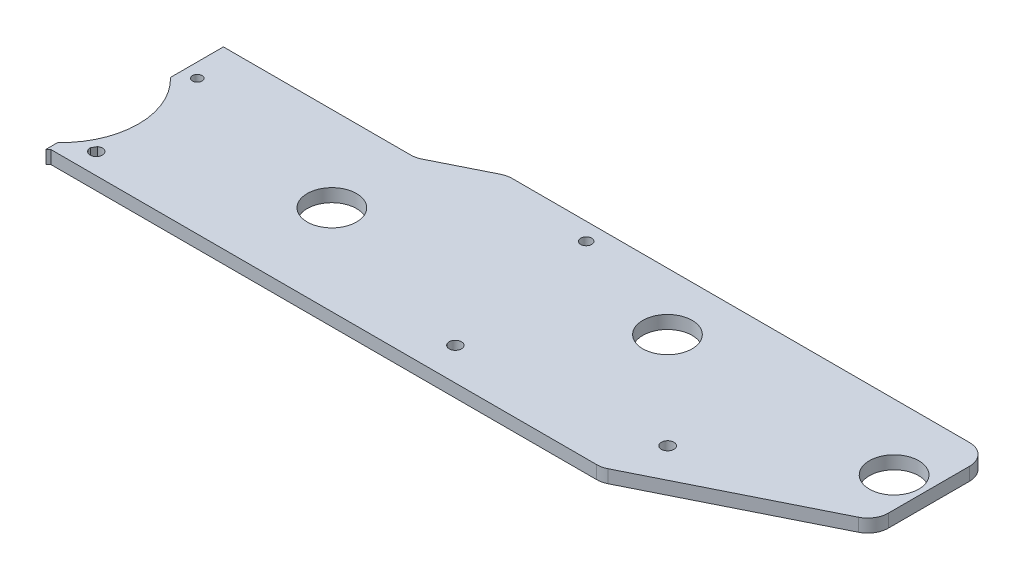
SolidWorks part; units mm, degrees
ref_plane "Front" through (0, 0, 0) normal (0, 0, 1) x (1, 0, 0)
ref_plane "Top" through (0, 0, 0) normal (0, 1, 0) x (1, 0, 0)
ref_plane "Right" through (0, 0, 0) normal (1, 0, 0) x (0, 0, -1)
sketch "Sketch1" plane through (0, 0, 0) normal (0, 1, 0) x (1, 0, 0)
  line L1 (0, 0) -> (210, 0)
  line L2 (0, 0) -> (0, -50)
  line L3 (0, -50) -> (210, -50)
  line L4 (210, 0) -> (210, -50)
  circle A7 centre (3.4895, -16.7877) radius 1.2117
  circle A8 centre (34.3726, -17.194) radius 1.1656
  circle A9 centre (37.5207, -44.9212) radius 1.5
  circle A12 centre (168.9752, -37.4032) radius 1.5173
  circle A13 centre (116, -4.2372) radius 1.3356
  circle A14 centre (12.2576, -3.2748) radius 1.6244
  dimension "D1" = 210
  dimension "D2" = 50
extrude "Boss-Extrude1" add sketch "Sketch1" along normal blind 3.175
sketch "Sketch2" plane through (0, 3.175, 0) normal (0, 1, 0) x (1, 0, 0)
  line L0 (210, 0) -> (0, 0) construction
  line L1 (0, 0) -> (0, -50) construction
  circle A0 centre (10, -26) radius 2
  circle A1 centre (10, -42) radius 2
  circle A2 centre (26, -26) radius 2
  circle A3 centre (26, -42) radius 2
  dimension "D1" = 16
  dimension "D2" = 16
  dimension "D3" = 16
  dimension "D4" = 26
  dimension "D5" = 10
  dimension "D6" = 10
  dimension "D7" = 26
  dimension "D8" = 16
extrude "Cut-Extrude1" cut sketch "Sketch2" against normal blind 10
sketch "Sketch3" plane through (0, 3.175, 0) normal (0, 1, 0) x (1, 0, 0)
  line L0 (210, 0) -> (0, 0) construction
  line L1 (210, 0) -> (0, 0) construction
  circle A0 centre (78.0103, -28.1) radius 6
  circle A1 centre (145.5313, -14) radius 6
  circle A2 centre (18, -34) radius 0.587
  circle A3 centre (26, -26) radius 2 construction
  circle A4 centre (202.6463, -16) radius 6
  dimension "D1" = 28.1
  dimension "D3" = 16
  dimension "D4" = 14
  dimension "D7" = 125.222
  dimension "D2" = 60.2996
  dimension "D5" = 8
  dimension "D6" = 8
  dimension "D8" = 57.15
extrude "Cut-Extrude2" cut sketch "Sketch3" against normal blind 57.15
sketch "Sketch4" [suppressed] plane through (0, 3.175, 0) normal (0, 1, 0) x (1, 0, 0)
  line L0 (3.4895, -16.7877) -> (18, -34)
  line L1 (3.4895, -20.6627) -> (5.9498, -23.5811)
  line L2 (18, -34) -> (34.3726, -17.194)
  line L3 (34.3726, -17.194) -> (75.8499, -28.1)
  line L4 (75.8499, -28.1) -> (37.5207, -44.9212)
  line L5 (7.3432, -17.194) -> (9.8664, -20.303)
  circle A0 centre (18, -34) radius 15.9299
  circle A1 centre (3.4895, -16.7877) radius 3.8751
  circle A2 centre (34.3726, -17.194) radius 3.7227
  circle A3 centre (37.5207, -44.9212) radius 3.8676
  circle A4 centre (75.8499, -28.1) radius 12.797
  circle A5 centre (112.3021, -4.7393) radius 5.1588
  circle A6 centre (118.879, -40.0177) radius 4.9035
  circle A7 centre (140.772, -16) radius 12.6375
  circle A8 centre (168.9752, -37.4032) radius 4.2066
  circle A9 centre (197.922, -16) radius 12.8
sketch "Sketch5" [suppressed] plane through (0, 3.175, 0) normal (0, 1, 0) x (1, 0, 0)
  line L0 (210, 0) -> (0, 0) construction
  line L2 (-0.6266, -16.7877) -> (37.5207, -16.7877)
  line L3 (-0.6266, -16.7877) -> (-0.6266, -44.9212)
  line L4 (-0.6266, -44.9212) -> (37.5207, -44.9212)
  line L5 (37.5207, -16.7877) -> (37.5207, -44.9212)
  line L6 (75.8499, -15.182) -> (37.5207, -15.182)
  line L7 (75.8499, -15.182) -> (75.8499, -44.9212)
  line L8 (75.8499, -44.9212) -> (37.5207, -44.9212)
  line L9 (37.5207, -15.182) -> (37.5207, -44.9212)
  line L10 (112.3021, -4.7393) -> (75.8499, -4.7393)
  line L11 (112.3021, -4.7393) -> (112.3021, -44.9212)
  line L12 (112.3021, -44.9212) -> (75.8499, -44.9212)
  line L13 (75.8499, -4.7393) -> (75.8499, -44.9212)
  line L14 (112.3021, -4.7393) -> (102.3945, -4.7393)
  line L16 (112.3021, -4.7393) -> (112.3021, 0)
  line L17 (112.3021, 0) -> (102.3945, 0)
  line L18 (102.3945, -4.7393) -> (102.3945, 0)
  line L19 (210, -50) -> (210, 0) construction
  line L20 (112.3021, -4.7393) -> (123.1553, -4.7393)
  line L21 (112.3021, -4.7393) -> (112.3021, 0)
  line L22 (112.3021, 0) -> (123.1553, 0)
  line L23 (123.1553, -4.7393) -> (123.1553, 0)
  line L24 (112.3021, -4.7393) -> (140.772, -4.7393)
  line L25 (112.3021, -4.7393) -> (112.3021, -40.0177)
  line L26 (112.3021, -40.0177) -> (140.772, -40.0177)
  line L27 (140.772, -4.7393) -> (140.772, -40.0177)
  line L28 (140.772, -16) -> (168.9752, -16)
  line L29 (140.772, -16) -> (140.772, -40.0177)
  line L30 (140.772, -40.0177) -> (168.9752, -40.0177)
  line L31 (168.9752, -16) -> (168.9752, -40.0177)
  line L32 (168.9752, -4.7393) -> (210, -4.7393)
  line L33 (168.9752, -4.7393) -> (168.9752, -40.0177)
  line L34 (168.9752, -40.0177) -> (210, -40.0177)
  line L35 (210, -4.7393) -> (210, -40.0177)
  line L36 (0, -50) -> (210, -50) construction
  line L37 (160.7629, -40.0177) -> (177.2091, -40.0177)
  line L38 (160.7629, -40.0177) -> (160.7629, -44.9212)
  line L39 (160.7629, -44.9212) -> (177.2091, -44.9212)
  line L40 (177.2091, -40.0177) -> (177.2091, -44.9212)
  line L41 (112.3021, -40.0177) -> (126.3591, -40.0177)
  line L42 (112.3021, -40.0177) -> (112.3021, -47.7828)
  line L43 (112.3021, -47.7828) -> (126.3591, -47.7828)
  line L44 (126.3591, -40.0177) -> (126.3591, -47.7828)
  line L45 (30.5963, -44.9212) -> (44.6115, -44.9212)
  line L46 (30.5963, -44.9212) -> (30.5963, -50)
  line L47 (30.5963, -50) -> (44.6115, -50)
  line L48 (44.6115, -44.9212) -> (44.6115, -50)
  line L50 (-0.6266, -44.9212) -> (30.5963, -44.9212)
  line L51 (-0.6266, -44.9212) -> (-0.6266, -50)
  line L52 (-0.6266, -50) -> (30.5963, -50)
  line L53 (30.5963, -44.9212) -> (30.5963, -50)
  circle A0 centre (3.4895, -16.7877) radius 4.1161
  circle A1 centre (34.3726, -17.194) radius 3.8132
  circle A2 centre (75.8499, -28.1) radius 12.918
  circle A3 centre (112.3021, -4.7393) radius 5.2663
  circle A4 centre (140.772, -16) radius 13.0245
  circle A5 centre (197.922, -16) radius 12.3805
  circle A6 centre (168.9752, -37.4032) radius 4.7643
  circle A7 centre (118.879, -40.0177) radius 5.279
  circle A8 centre (37.5207, -44.9212) radius 4.2049
  line M12 (0, 0) -> (0, -50)
  line M13 (0, -50) -> (210, -50)
  line M14 (210, -50) -> (210, 0)
  line M15 (210, 0) -> (0, 0)
extrude "Cut-Extrude5" [suppressed] cut sketch "Sketch5" against normal blind 11.52 contours A5 L32 L23 L24 A4 L28 L33 M14 M15 | A1 L6 L13 L10 L18 A0 L2 M15 M12 | L8 L48 L34 L40 L39 L38 L30 L26 L44 L43 L42 L12 M13 M14
fillet "Fillet1" [suppressed] radius 5
sketch "Sketch10" plane through (0, 3.175, 0) normal (0, 1, 0) x (1, 0, 0)
  line L0 (210, -27.8594) -> (165.5029, -50)
  line L1 (210, -50) -> (210, 0) construction
  line L2 (0, -50) -> (210, -50) construction
  line L3 (165.5029, -50) -> (210, -50)
  line L4 (210, -50) -> (210, -27.8594)
  line L5 (92.5326, 0) -> (77.6548, -7.4028)
  line L6 (210, 0) -> (0, 0) construction
  line L7 (77.6548, -7.4028) -> (0, -7.4028)
  line L8 (0, 0) -> (0, -50) construction
  line L9 (0, -7.4028) -> (0, 0)
  line L10 (0, 0) -> (92.5326, 0)
extrude "Cut-Extrude7" cut sketch "Sketch10" against normal blind 10
fillet "Fillet3" radius 5 7 edges at (0, 1.5875, 50) (0, 1.5875, 7.4028) (77.6548, 1.5875, 7.4028) (92.5326, 1.5875, 0) (210, 1.5875, 0) (210, 1.5875, 27.8594) (165.5029, 1.5875, 50)
sketch "Sketch11" plane through (0, 3.175, 0) normal (0, 1, 0) x (1, 0, 0)
  circle A0 centre (18, -34) radius 18.5
  circle A1 centre (10, -26) radius 2
  circle A2 centre (10, -42) radius 2
  circle A3 centre (26, -26) radius 2
  circle A4 centre (26, -42) radius 2
extrude "Boss-Extrude4" add sketch "Sketch11" against normal blind 3.175
sketch "Sketch12" plane through (0, 3.175, 0) normal (0, 1, 0) x (1, 0, 0)
  circle A0 centre (18, -34) radius 21
  circle A1 centre (10, -26) radius 2 construction
  circle A2 centre (10, -42) radius 2 construction
  dimension "D1" = 8
  dimension "D2" = 8
extrude "Boss-Extrude5" add sketch "Sketch12" against normal blind 3.175
sketch "Sketch13" plane through (0, 3.175, 0) normal (0, 1, 0) x (1, 0, 0)
  circle A0 centre (18, -34) radius 18.85
extrude "Cut-Extrude8" cut sketch "Sketch13" against normal blind 3.175
sketch "Sketch14" plane through (0, 3.175, 0) normal (0, 1, 0) x (1, 0, 0)
  line L0 (0, -12.4028) -> (0, -23.1833) construction
  line L1 (0, -34.2728) -> (-35.83, -34.2728)
  line L2 (0, -34.2728) -> (0, 0.7272)
  line L3 (0, 0.7272) -> (-35.83, 0.7272)
  line L4 (-35.83, -34.2728) -> (-35.83, 0.7272)
  line L5 (5, -7.4028) -> (76.4796, -7.4028) construction
  line L8 (0, 0.7272) -> (18, 0.7272)
  line L9 (0, 0.7272) -> (0, -12.2485)
  line L10 (0, -12.2485) -> (18, -12.2485)
  line L11 (18, 0.7272) -> (18, -12.2485)
  line M20 (76.4796, -7.4028) -> (5, -7.4028)
  arc M21 (5, -7.4028) -> (0, -12.4028) centre (5, -12.4028) ccw
  line M22 (0, -12.4028) -> (0, -23.1833)
  arc M23 (0, -23.1833) -> (0, -44.8167) centre (18, -34) ccw
  dimension "D4" = 18
  dimension "D1" = 8.13
  dimension "D2" = 35.83
  dimension "D3" = 35
extrude "Boss-Extrude6" add sketch "Sketch14" against normal blind 3.175 contours L4 L1 L2 L3 M23 M22 | L11 L8 L2 L10 M21 M20
fillet "Fillet4" radius 5 3 edges at (18, 1.5875, -0.7272) (-35.83, 1.5875, 34.2728) (-35.83, 1.5875, -0.7272)
sketch "Sketch15" plane through (0, 3.175, 0) normal (0, 1, 0) x (1, 0, 0)
  line L0 (210, -24.7625) -> (210, -5) construction
  circle A0 centre (122, -42.0581) radius 1.5
  dimension "D1" = 88
extrude "Cut-Extrude9" cut sketch "Sketch15" against normal blind 10
sketch "Sketch16" plane through (0, 3.175, 0) normal (0, 1, 0) x (1, 0, 0)
  line L0 (18, -4.2728) -> (18, -7.4028) construction
  line L1 (13, 0.7272) -> (-30.83, 0.7272) construction
  circle A0 centre (12, -3.2728) radius 1.5
  dimension "D1" = 6
  dimension "D2" = 4
extrude "Cut-Extrude10" cut sketch "Sketch16" against normal blind 10
sketch "Sketch17" plane through (0, 3.175, 0) normal (0, 1, 0) x (1, 0, 0)
  line L3 (-51.8835, 9.8769) -> (30.9276, 9.8769)
  line L4 (-51.8835, 9.8769) -> (-51.8835, -56.6458)
  line L5 (-51.8835, -56.6458) -> (30.9276, -56.6458)
  line L6 (30.9276, 9.8769) -> (30.9276, -56.6458)
  point P10 (0, 0)
extrude "Cut-Extrude11" cut sketch "Sketch17" against normal blind 10
